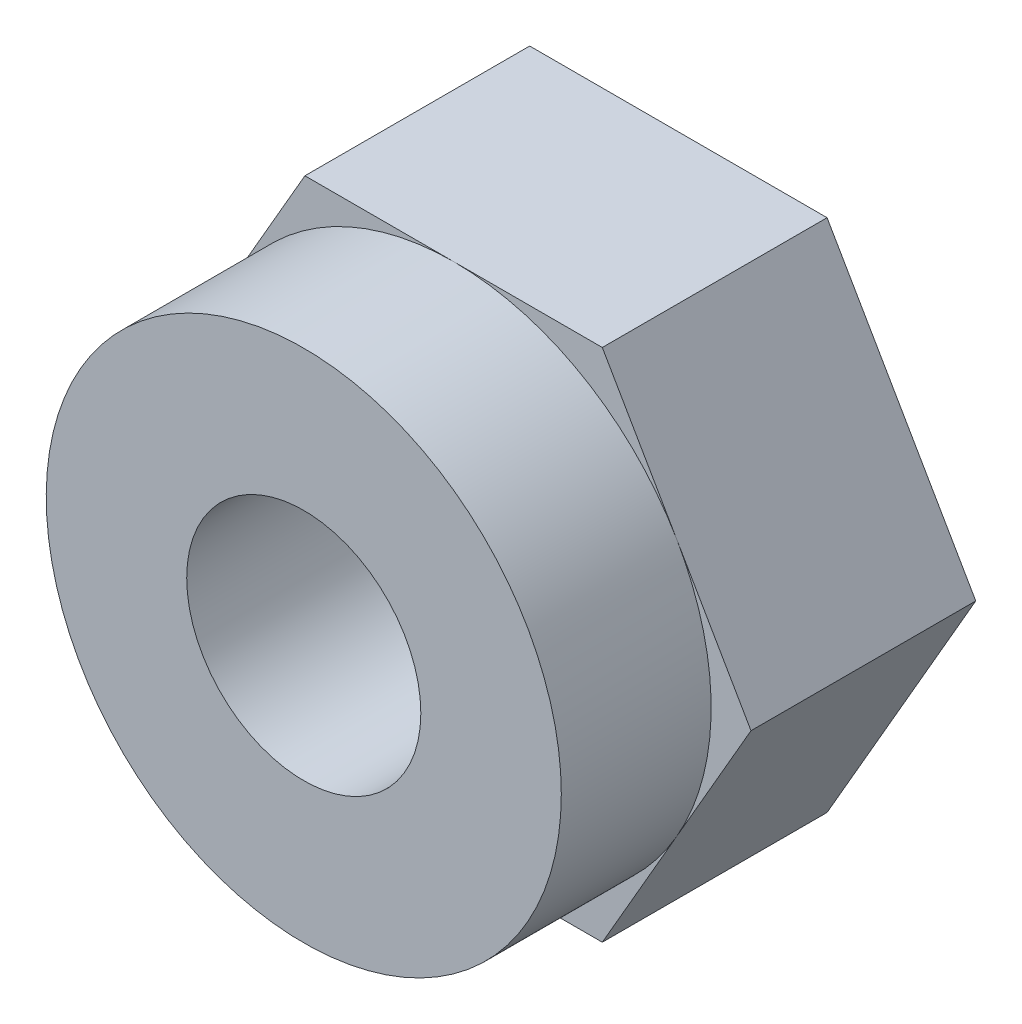
SolidWorks part; units mm, degrees
material "Acier allié inoxydable"
ref_plane "Plan de face" through (0, 0, 0) normal (0, 0, 1) x (1, 0, 0)
ref_plane "Plan de dessus" through (0, 0, 0) normal (0, 1, 0) x (1, 0, 0)
ref_plane "Plan de droite" through (0, 0, 0) normal (1, 0, 0) x (0, 0, -1)
sketch "Esquisse1" plane through (0, 0, 0) normal (0, 0, 1) x (1, 0, 0)
  line L1 (3.1754, 0) -> (1.5877, 2.75)
  line L2 (1.5877, 2.75) -> (-1.5877, 2.75)
  line L3 (-1.5877, 2.75) -> (-3.1754, 0)
  line L4 (-3.1754, 0) -> (-1.5877, -2.75)
  line L5 (-1.5877, -2.75) -> (1.5877, -2.75)
  line L6 (1.5877, -2.75) -> (3.1754, 0)
  circle A0 centre (0, 0) radius 1.25
  circle A1 centre (0, 0) radius 2.75 construction
  dimension "D1" = 5.5
  dimension "D2" = 2.5
extrude "Boss.-Extru.1" add sketch "Esquisse1" along normal blind 2.4
sketch "Esquisse2" plane through (0, 0, 0) normal (0, 0, 1) x (1, 0, 0)
  line L0 (3.1754, 0) -> (1.5877, 2.75) construction
  circle A0 centre (0, 0) radius 2.75
  circle A1 centre (0, 0) radius 1.25 construction
  circle A2 centre (0, 0) radius 1.25
extrude "Boss.-Extru.2" add sketch "Esquisse2" along normal blind 4
